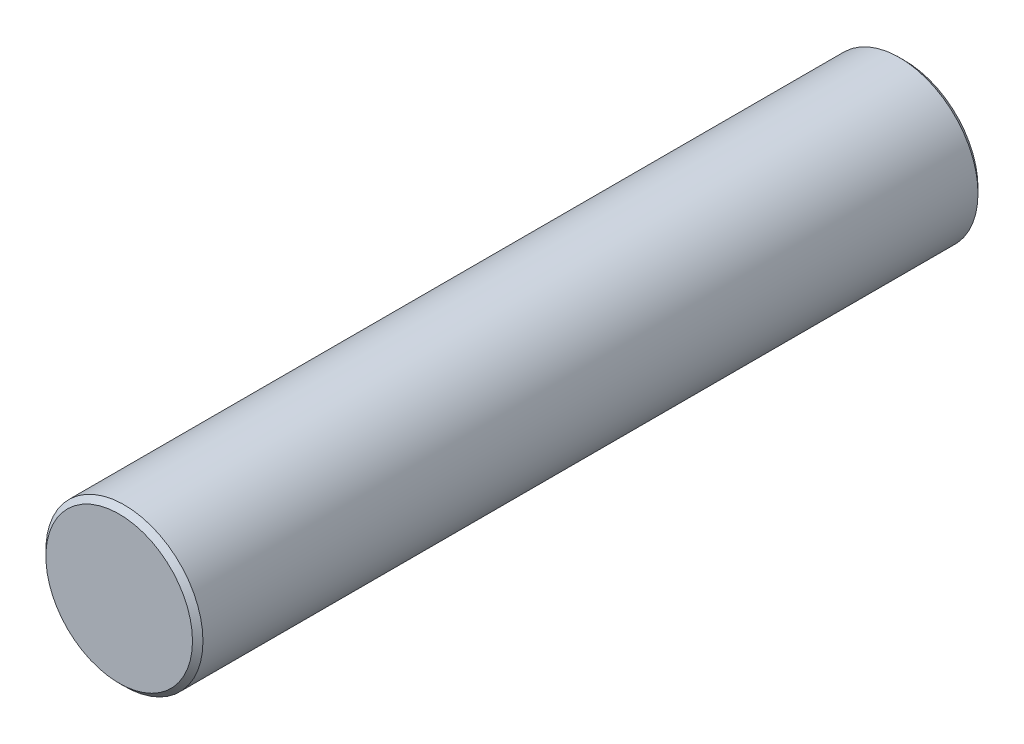
SolidWorks part; units mm, degrees
ref_plane "Plan de face" through (0, 0, 0) normal (0, 0, 1) x (1, 0, 0)
ref_plane "Plan de dessus" through (0, 0, 0) normal (0, 1, 0) x (1, 0, 0)
ref_plane "Plan de droite" through (0, 0, 0) normal (1, 0, 0) x (0, 0, -1)
sketch "Esquisse1" plane through (0, 0, 0) normal (0, 0, 1) x (1, 0, 0)
  circle A0 centre (0, 0) radius 1.5
  dimension "D1" = 3
extrude "Boss.-Extru.1" add sketch "Esquisse1" along normal blind 15
chamfer "Chanfrein1" distance 0.1 angle 45 2 edges at (1.5, 0, 15) (1.5, 0, 0)
